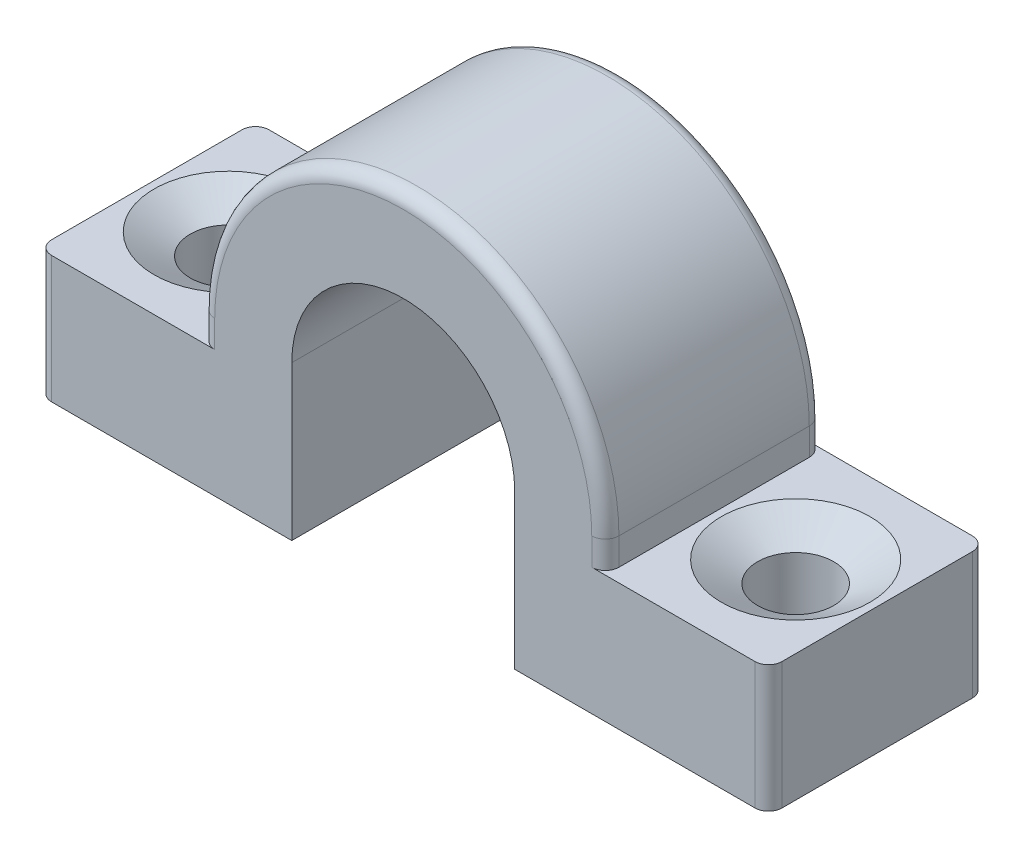
SolidWorks part; units mm, degrees
ref_plane "Front Plane" through (0, 0, 0) normal (0, 0, 1) x (1, 0, 0)
ref_plane "Top Plane" through (0, 0, 0) normal (0, 1, 0) x (1, 0, 0)
ref_plane "Right Plane" through (0, 0, 0) normal (1, 0, 0) x (0, 0, -1)
sketch "Sketch1" plane through (0, 0, 0) normal (0, 0, 1) x (1, 0, 0)
  line L0 (-11.15, 0) -> (-11.15, -1.5)
  line L1 (-11.15, -1.5) -> (-20.15, -1.5)
  line L2 (-20.15, -1.5) -> (-20.15, -8.5)
  line L3 (-20.15, -8.5) -> (-6.15, -8.5)
  line L4 (-6.15, -8.5) -> (-6.15, 0)
  line L5 (6.15, 0) -> (6.15, -8.5)
  line L6 (6.15, -8.5) -> (20.15, -8.5)
  line L7 (20.15, -8.5) -> (20.15, -1.5)
  line L8 (20.15, -1.5) -> (11.15, -1.5)
  line L9 (11.15, -1.5) -> (11.15, 0)
  arc A0 (6.15, 0) -> (-6.15, 0) centre (0, 0) ccw
  arc A1 (11.15, 0) -> (-11.15, 0) centre (0, 0) ccw
  dimension "D1" = 12.3
  dimension "D2" = 5
  dimension "D3" = 7
  dimension "D4" = 14
  dimension "D5" = 8.5
extrude "Boss-Extrude1" add sketch "Sketch1" along normal blind 12
sketch "Sketch4" plane through (0, -1.5, 0) normal (0, 1, 0) x (1, 0, 0)
  line L0 (-11.15, 0) -> (-20.15, 0) construction
  line L1 (-20.15, -12) -> (-20.15, 0) construction
  line L2 (20.15, 0) -> (11.15, 0) construction
  line L3 (20.15, -12) -> (20.15, 0) construction
  circle A0 centre (-15.65, -6) radius 2.1
  circle A1 centre (15.65, -6) radius 2.1
  point P4 (-15.65, 0)
  point P7 (-20.15, -6)
  point P12 (15.65, 0)
  point P15 (20.15, -6)
  dimension "D1" = 4.2
extrude "Cut-Extrude1" cut sketch "Sketch4" against normal through all
chamfer "Chamfer1" distance 2 angle 30 2 edges at (13.55, -1.5, 6) (-17.75, -1.5, 6)
fillet "Fillet2" radius 0.75 10 edges at (20.15, -5, 0) (20.15, -5, 12) (-20.15, -5, 0) (-20.15, -5, 12) (11.15, -0.75, 0) (-11.15, -0.75, 0) (11.15, -0.75, 12) (-11.15, -0.75, 12) (0, 11.15, 0) (0, 11.15, 12)
